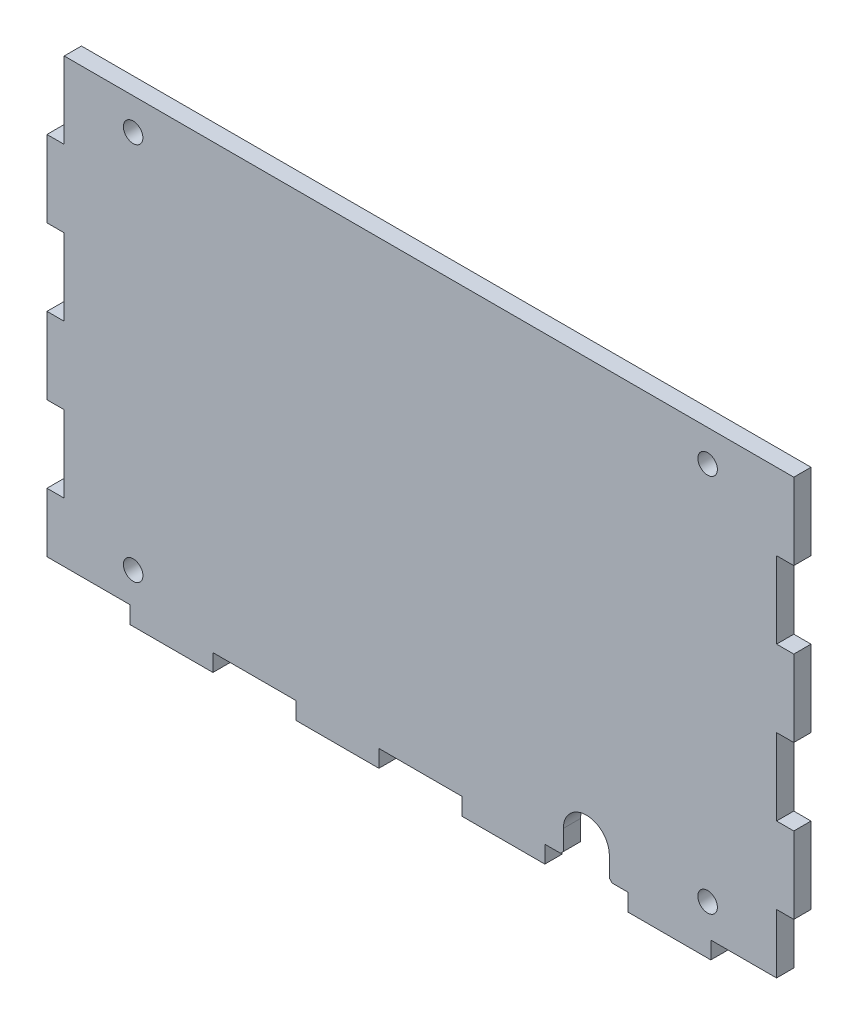
SolidWorks part; units mm, degrees
material "Acrylic (Medium-high impact)"
ref_plane "Front Plane" through (0, 0, 0) normal (0, 0, 1) x (1, 0, 0)
ref_plane "Top Plane" through (0, 0, 0) normal (0, 1, 0) x (1, 0, 0)
ref_plane "Right Plane" through (0, 0, 0) normal (1, 0, 0) x (0, 0, -1)
sketch "Sketch1" plane through (0, 0, 0) normal (0, 0, 1) x (1, 0, 0)
  line L1 (0, 0) -> (130, 0)
  line L2 (0, 0) -> (0, 80)
  line L3 (0, 80) -> (130, 80)
  line L4 (130, 0) -> (130, 80)
  dimension "D1" = 130
  dimension "D2" = 80
extrude "Boss-Extrude1" add sketch "Sketch1" along normal blind 3
sketch "Sketch2" plane through (0, 0, 3) normal (0, 0, 1) x (1, 0, 0)
  line L61 (14.4444, 3) -> (28.8889, 3) construction
  line L62 (0, 0) -> (14.4444, 0)
  line L67 (0, 0) -> (0, 3)
  line L72 (0, 3) -> (14.4444, 3)
  line L77 (14.4444, 0) -> (14.4444, 3)
  line L97 (28.8889, 0) -> (28.8889, 3)
  line L98 (28.8889, 0) -> (43.3333, 0)
  line L107 (43.3333, 0) -> (43.3333, 3)
  line L115 (28.8889, 3) -> (43.3333, 3)
  line L117 (43.3333, 3) -> (57.7778, 3) construction
  line L123 (57.7778, 0) -> (57.7778, 3)
  line L128 (57.7778, 0) -> (72.2222, 0)
  line L129 (72.2222, 0) -> (72.2222, 3)
  line L131 (57.7778, 3) -> (72.2222, 3)
  line L132 (72.2222, 3) -> (86.6667, 3) construction
  line L133 (86.6667, 0) -> (86.6667, 3)
  line L134 (86.6667, 0) -> (101.1111, 0)
  line L135 (101.1111, 0) -> (101.1111, 3)
  line L136 (86.6667, 3) -> (101.1111, 3)
  line L137 (101.1111, 3) -> (115.5556, 3) construction
  line L138 (115.5556, 0) -> (115.5556, 3)
  line L139 (115.5556, 0) -> (130, 0)
  line L142 (130, 0) -> (130, 80) construction
  line L143 (0, 80) -> (0, 0) construction
  line L144 (0, 13.3333) -> (3, 13.3333)
  line L145 (0, 13.3333) -> (0, 26.6667)
  line L146 (130, 3) -> (144.4444, 3) construction
  line L147 (0, 26.6667) -> (3, 26.6667)
  line L148 (3, 13.3333) -> (3, 26.6667)
  line L149 (3, 13.3333) -> (3, 0) construction
  line L150 (0, 40) -> (0, 53.3333)
  line L151 (0, 40) -> (3, 40)
  line L152 (3, 40) -> (3, 53.3333)
  line L153 (0, 53.3333) -> (3, 53.3333)
  line L154 (3, 40) -> (3, 26.6667) construction
  line L155 (0, 66.6667) -> (0, 80)
  line L156 (0, 66.6667) -> (3, 66.6667)
  line L157 (3, 66.6667) -> (3, 80)
  line L158 (0, 80) -> (3, 80)
  line L159 (3, 66.6667) -> (3, 53.3333) construction
  line L160 (130, 80) -> (0, 80) construction
  line L161 (127, 80) -> (127, 66.6667) construction
  line L162 (127, 40) -> (127, 26.6667)
  line L163 (127, 66.6667) -> (130, 66.6667)
  line L164 (127, 66.6667) -> (127, 53.3333)
  line L165 (127, 53.3333) -> (130, 53.3333)
  line L166 (130, 66.6667) -> (130, 53.3333)
  line L167 (127, 40) -> (130, 40)
  line L168 (130, 40) -> (130, 26.6667)
  line L169 (127, 26.6667) -> (130, 26.6667)
  line L170 (127, 53.3333) -> (127, 40) construction
  line L172 (127, 13.3333) -> (130, 13.3333)
  line L173 (130, 13.3333) -> (130, 0)
  line L175 (127, 26.6667) -> (127, 13.3333) construction
  line L183 (115.5556, 3) -> (130, 3) [skipped]
  line L184 (130, 0) -> (130, 3) [skipped]
  line L185 (127, 13.3333) -> (127, 3)
  line L186 (127, 3) -> (115.5556, 3)
  line L187 (127, 0) -> (130, 0) [skipped]
  line L188 (127, 13.3333) -> (127, 0) [skipped]
  dimension "D2" = 3
  dimension "D4" = 3
  dimension "D6" = 3
  dimension "D1" = 5
  dimension "D3" = 3
  dimension "D5" = 3
extrude "Cut tabs" cut sketch "Sketch2" against normal through all
sketch "Sketch3" plane through (0, 0, 3) normal (0, 0, 1) x (1, 0, 0)
  line L0 (0, 66.6667) -> (0, 53.3333) construction
  line L1 (130, 80) -> (3, 80) construction
  line L2 (0, 66.6667) -> (130, 66.6667) construction
  line L3 (65, 66.6667) -> (65, 50066.6667) construction
  line L4 (14.4444, 3) -> (0, 3) construction
  line L5 (15, 74.5) -> (115, 74.5) construction
  line L6 (15, 74.5) -> (15, 8.5) construction
  line L7 (15, 8.5) -> (115, 8.5) construction
  line L8 (115, 74.5) -> (115, 8.5) construction
  circle A0 centre (15, 74.5) radius 1.7
  circle A1 centre (115, 74.5) radius 1.7
  circle A2 centre (15, 8.5) radius 1.7
  circle A3 centre (115, 8.5) radius 1.7
  point P10 (65, 66.6667)
  dimension "D1" = 3.4
  dimension "D2" = 15
  dimension "D3" = 5.5
  dimension "D4" = 5.5
extrude "Cut cornerpiece holes" cut sketch "Sketch3" against normal up to next
sketch "Sketch4" plane through (0, 0, 0) normal (0, 0, -1) x (-1, 0, 0)
  line L0 (-97.8889, 3) -> (-97.8889, 7)
  line L1 (-101.1111, 3) -> (-86.6667, 3) construction
  line L2 (-89.8889, 3) -> (-89.8889, 7)
  line L3 (-97.8889, 3) -> (-89.8889, 3)
  line L4 (-101.1111, 0) -> (-86.6667, 0) construction
  line L5 (-101.1111, 0) -> (-115.5556, 0) construction
  line L6 (-101.1111, 0) -> (-101.1111, 3) construction
  line L7 (-72.2222, 0) -> (-86.6667, 0) construction
  arc A0 (-97.8889, 7) -> (-89.8889, 7) centre (-93.8889, 7) cw
  point P15 (-93.8889, 0)
  dimension "D2" = 8
  dimension "D1" = 8
extrude "Cut power cord clearance" cut sketch "Sketch4" against normal up to next
chamfer "Chamfer1" distance 0.5 angle 45 2 edges at (89.8889, 3, 1.5) (97.8889, 3, 1.5)
other "Width tolerance" face at (1.5, 53.3333, 1.5) face at (1.5, 26.6667, 1.5) face at (1.5, 13.3333, 1.5) face at (1.5, 40, 1.5) face at (1.5, 66.6667, 1.5) face at (14.4444, 1.5, 1.5) face at (43.3333, 1.5, 1.5) face at (72.2222, 1.5, 1.5) face at (101.1111, 1.5, 1.5) face at (28.8889, 1.5, 1.5) face at (57.7778, 1.5, 1.5) face at (86.6667, 1.5, 1.5) face at (115.5556, 1.5, 1.5) face at (128.5, 13.3333, 1.5) face at (128.5, 66.6667, 1.5) face at (128.5, 40, 1.5) face at (128.5, 26.6667, 1.5) face at (128.5, 53.3333, 1.5) parameters "D1"=0
equation "\"wall_thickness\"= 3mm"
equation "\"D1@Boss-Extrude1\"=\"wall_thickness\""
equation "\"slot_width_tolerance\"= 0.0mm"
equation "\"slot_depth\"= 3mm"
equation "\"D2@Sketch2\"=\"slot_depth\""
equation "\"D4@Sketch2\"=\"slot_depth\""
equation "\"D6@Sketch2\"=\"slot_depth\""
equation "\"D2@Sketch3\"=\"wall_thickness\"+12mm"
equation "\"D1@Width tolerance\"=\"slot_width_tolerance\""
